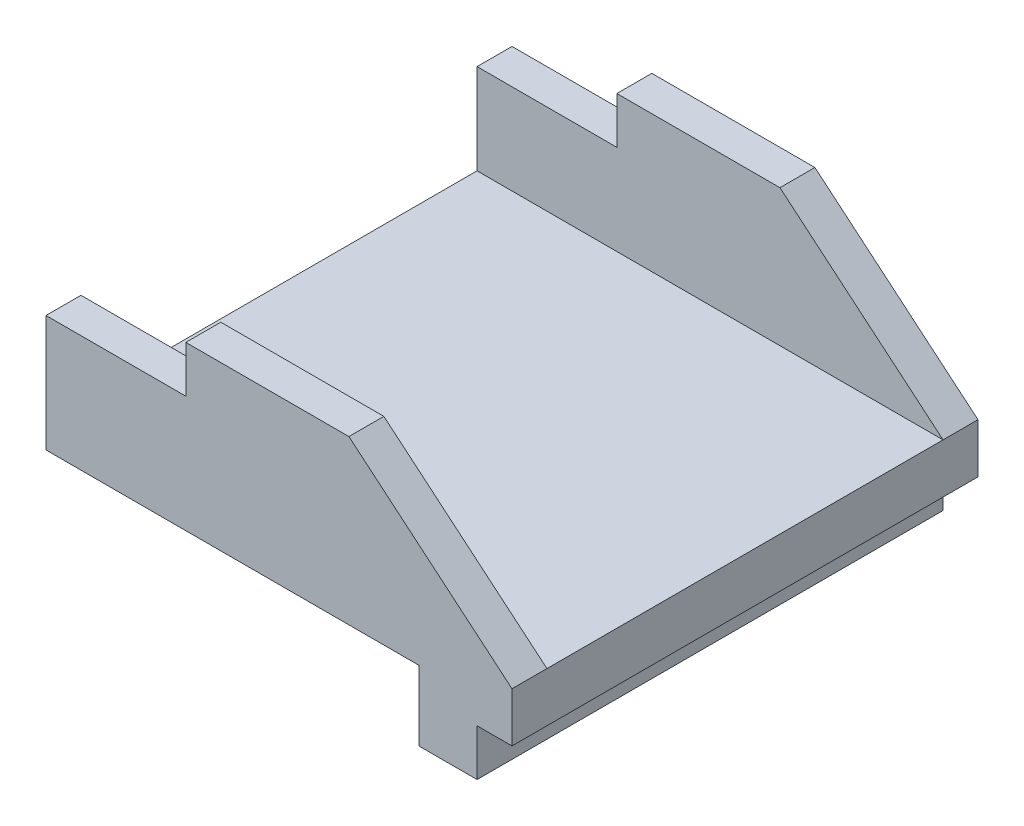
SolidWorks part; units mm, degrees
ref_plane "Спереди" through (0, 0, 0) normal (0, 0, 1) x (1, 0, 0)
ref_plane "Сверху" through (0, 0, 0) normal (0, 1, 0) x (1, 0, 0)
ref_plane "Справа" through (0, 0, 0) normal (1, 0, 0) x (0, 0, -1)
sketch "Эскиз1" plane through (0, 0, 0) normal (0, 0, 1) x (1, 0, 0)
  line L1 (10, -5) -> (-10, -5)
  line L2 (10, -5) -> (10, 5)
  line L3 (10, 5) -> (-10, 5)
  line L4 (-10, -5) -> (-10, 5)
  line L5 (10, -5) -> (-10, 5) construction
  line L6 (10, 5) -> (-10, -5) construction
  point P0 (0, 0)
  dimension "D1" = 10
  dimension "D2" = 20
extrude "Бобышка-Вытянуть2" add sketch "Эскиз1" along normal mid plane 20
sketch "Эскиз2" plane through (0, 0, 10) normal (0, 0, 1) x (1, 0, 0)
  line L0 (-10, -2) -> (6, -2)
  line L1 (-10, 5) -> (-10, -5) construction
  line L2 (6, -2) -> (6, -5)
  line L3 (-10, -5) -> (10, -5) construction
  line L4 (6, -5) -> (8.5, -5)
  line L5 (8.5, -5) -> (8.5, -3)
  line L6 (8.5, -3) -> (10, -3)
  line L7 (10, -5) -> (10, 5) construction
  line L8 (-10, 3) -> (-4, 3)
  line L9 (-4, 3) -> (-4, 5)
  line L10 (10, 5) -> (-10, 5) construction
  line L11 (3, 5) -> (10, -0.8737)
  line M8 (-10, 5) -> (-10, -5)
  line M9 (-10, -5) -> (10, -5)
  line M10 (10, -5) -> (10, 5)
  line M11 (10, 5) -> (-10, 5)
  dimension "D1" = 16
  dimension "D2" = 3
  dimension "D3" = 2
  dimension "D4" = 1.5
  dimension "D5" = 50
  dimension "D6" = 7
  dimension "D7" = 2
  dimension "D8" = 6
extrude "Вырез-Вытянуть1" cut sketch "Эскиз2" against normal through all contours L8 L9 M11 M8 | L11 M11 M10 | L2 L0 M8 M9 | L6 L5 M9 M10
sketch "Эскиз7" plane through (0, 0, 0) normal (1, 0, 0) x (0, 0, -1)
  line L0 (0, 5) -> (0, -5) construction
  line L1 (10, 5) -> (-10, 5) construction
  line L2 (10, -5) -> (-10, -5) construction
  line L3 (-8.5, 5) -> (-8.5, -0.8737)
  line L4 (10, -0.8737) -> (-10, -0.8737) construction
  line L5 (8.5, 5) -> (8.5, -0.8737)
  line L6 (-8.5, -0.8737) -> (8.5, -0.8737)
  line L7 (-8.5, 5) -> (8.5, 5)
  dimension "D1" = 17
extrude "Вырез-Вытянуть2" cut sketch "Эскиз7" against normal blind 20 and the other way blind 20
